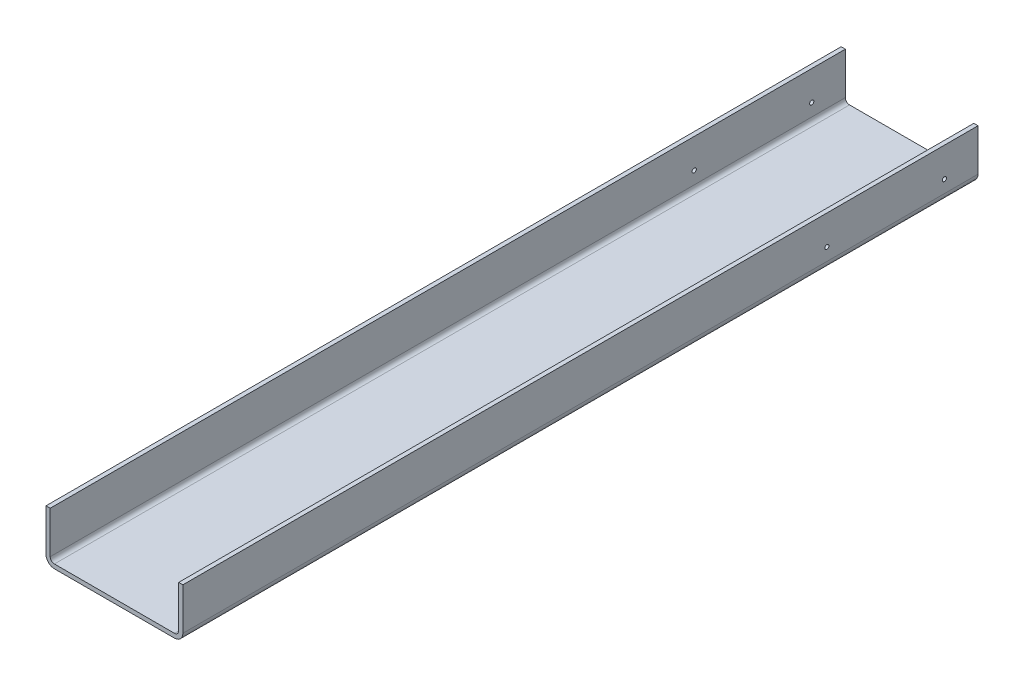
SolidWorks part; units mm, degrees
material "AISI 304"
ref_plane "Спереди" through (0, 0, 0) normal (0, 0, 1) x (1, 0, 0)
ref_plane "Сверху" through (0, 0, 0) normal (0, 1, 0) x (1, 0, 0)
ref_plane "Справа" through (0, 0, 0) normal (1, 0, 0) x (0, 0, -1)
sketch "Эскиз1" plane through (0, 0, 0) normal (0, 0, 1) x (1, 0, 0)
  line L0 (71.5, 0) -> (-71.5, 0)
  line L1 (-81.5, 10) -> (-81.5, 60)
  line L2 (0, -33) -> (0, 33) construction
  line L3 (81.5, 10) -> (81.5, 60)
  line L4 (76.5, 10) -> (76.5, 60)
  line L5 (71.5, 5) -> (-71.5, 5)
  line L6 (-76.5, 10) -> (-76.5, 60)
  line L7 (-81.5, 60) -> (-76.5, 60)
  line L8 (76.5, 60) -> (81.5, 60)
  line L9 (81.5, 0) -> (81.5, 60) construction
  line L10 (81.5, 0) -> (-81.5, 0) construction
  line L11 (-81.5, 0) -> (-81.5, 60) construction
  line L12 (76.5, 5) -> (76.5, 60) construction
  line L13 (76.5, 5) -> (-76.5, 5) construction
  line L14 (-76.5, 5) -> (-76.5, 60) construction
  arc A0 (81.5, 10) -> (71.5, 0) centre (71.5, 10) cw
  arc A1 (-71.5, 0) -> (-81.5, 10) centre (-71.5, 10) cw
  arc A2 (76.5, 10) -> (71.5, 5) centre (71.5, 10) cw
  arc A3 (-71.5, 5) -> (-76.5, 10) centre (-71.5, 10) cw
  point P7 (0, 0)
  point P15 (81.5, 0)
  dimension "D4" = 10
  dimension "D2" = 5
  dimension "D3" = 163
  dimension "D5" = 60
  dimension "D1" = 5
extrude "Бобышка-Вытянуть1" add sketch "Эскиз1" along normal mid plane 947
sketch "Эскиз2" plane through (-81.5, 0, 0) normal (-1, 0, 0) x (0, 0, 1)
  line L0 (-433.5, 24.9115) -> (-293.5, 24.9115) construction
  line L1 (473.5, 0) -> (-473.5, 0) construction
  line L2 (-473.5, 60) -> (-473.5, 10) construction
  circle A2 centre (-433.5, 24.9115) radius 2.5
  circle A3 centre (-293.5, 24.9115) radius 2.5
  dimension "D1" = 140
  dimension "D3" = 5
  dimension "D2" = 24.9115
  dimension "D4" = 40
extrude "Вырез-Вытянуть1" cut sketch "Эскиз2" against normal through all both and the other way through all
cosmetic thread "Условное изображение резьбы1" parameters "D2"=8
cosmetic thread "Условное изображение резьбы2" parameters "D2"=8
cosmetic thread "Условное изображение резьбы3" parameters "D2"=8
cosmetic thread "Условное изображение резьбы4" parameters "D2"=6
move or copy body "Тело-Переместить/Копировать2" [suppressed] bodies to move or copy 101 parameters "D1"=0, "D2"=0, "D3"=0
move or copy body "Тело-Переместить/Копировать1" [suppressed] bodies to move or copy 101 parameters "D1"=0, "D2"=0, "D3"=0
